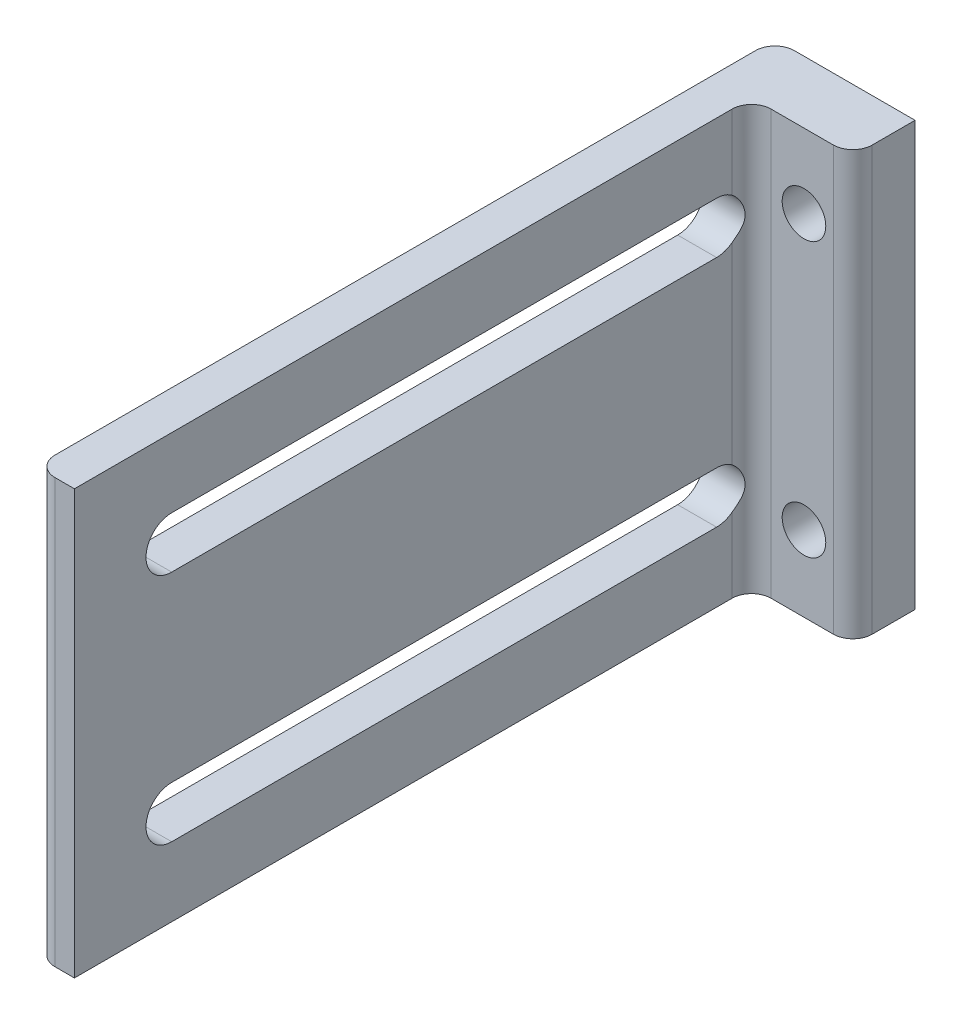
SolidWorks part; units mm, degrees
ref_plane "Front Plane" through (0, 0, 0) normal (0, 0, 1) x (1, 0, 0)
ref_plane "Top Plane" through (0, 0, 0) normal (0, 1, 0) x (1, 0, 0)
ref_plane "Right Plane" through (0, 0, 0) normal (1, 0, 0) x (0, 0, -1)
sketch "Sketch1" plane through (0, 0, 0) normal (0, 0, 1) x (1, 0, 0)
  line L0 (-44.365, 0) -> (-44.365, -29) construction
  line L1 (-44.365, -28.1053) -> (-53.365, -28.1053)
  line L2 (-44.365, -28.1053) -> (-44.365, -0.89)
  line L3 (-44.365, -0.89) -> (-53.365, -0.89)
  line L4 (-53.365, -28.1053) -> (-53.365, -0.89)
  line L5 (-46.7118, -0.89) -> (-40.7318, -0.89) construction
  arc A0 (-46.7118, -25.61) -> (-44.2118, -28.11) centre (-44.2118, -25.61) ccw construction
  dimension "D1" = 9
extrude "Boss-Extrude1" add sketch "Sketch1" along normal blind 4
sketch "Sketch2" plane through (0, 0, 4) normal (0, 0, 1) x (1, 0, 0)
  line L0 (-44.365, -0.89) -> (-53.365, -0.89) construction
  line L1 (-53.365, -28.1053) -> (-50.865, -28.1053)
  line L2 (-53.365, -28.1053) -> (-53.365, -0.89)
  line L3 (-53.365, -0.89) -> (-50.865, -0.89)
  line L4 (-50.865, -28.1053) -> (-50.865, -0.89)
  dimension "D1" = 2.5
extrude "Boss-Extrude2" add sketch "Sketch2" along normal blind 43.5
fillet "Fillet1" radius 1.25 4 edges at (-53.365, -14.4976, 0) (-50.865, -14.4976, 4) (-44.365, -14.4976, 4) (-53.365, -14.4976, 47.5)
sketch "Sketch6" plane through (-53.365, 0, 0) normal (-1, 0, 0) x (0, 0, 1)
  line L0 (23.75, -0.89) -> (23.75, -28.1053) construction
  line L1 (46.25, -0.89) -> (1.25, -0.89) construction
  line L2 (46.25, -28.1053) -> (1.25, -28.1053) construction
  line L3 (41.25, -22) -> (23.75, -22) construction
  line L4 (41.25, -7) -> (23.75, -7) construction
  line L5 (6.25, -22) -> (41.25, -22) construction
  line L6 (6.25, -20.35) -> (41.25, -20.35)
  line L7 (6.25, -23.65) -> (41.25, -23.65)
  line L8 (6.25, -7) -> (41.25, -7) construction
  line L9 (6.25, -5.35) -> (41.25, -5.35)
  line L10 (6.25, -8.65) -> (41.25, -8.65)
  arc A0 (6.25, -20.35) -> (6.25, -23.65) centre (6.25, -22) ccw
  arc A1 (41.25, -23.65) -> (41.25, -20.35) centre (41.25, -22) ccw
  arc A2 (6.25, -5.35) -> (6.25, -8.65) centre (6.25, -7) ccw
  arc A3 (41.25, -8.65) -> (41.25, -5.35) centre (41.25, -7) ccw
  point P13 (23.75, -22)
  point P19 (23.75, -7)
  dimension "D1" = 1.65
  dimension "D2" = 1.65
  dimension "D3" = 35
  dimension "D4" = 35
extrude "Cut-Extrude1" cut sketch "Sketch6" against normal up to next
sketch "Sketch7" plane through (0, 0, 4) normal (0, 0, 1) x (1, 0, 0)
  circle A0 centre (-47.5, -23.25) radius 1.4
  circle A1 centre (-47.5, -5.65) radius 1.4
  dimension "D1" = 2.8
  dimension "D2" = 2.8
extrude "Cut-Extrude2" cut sketch "Sketch7" against normal through all
